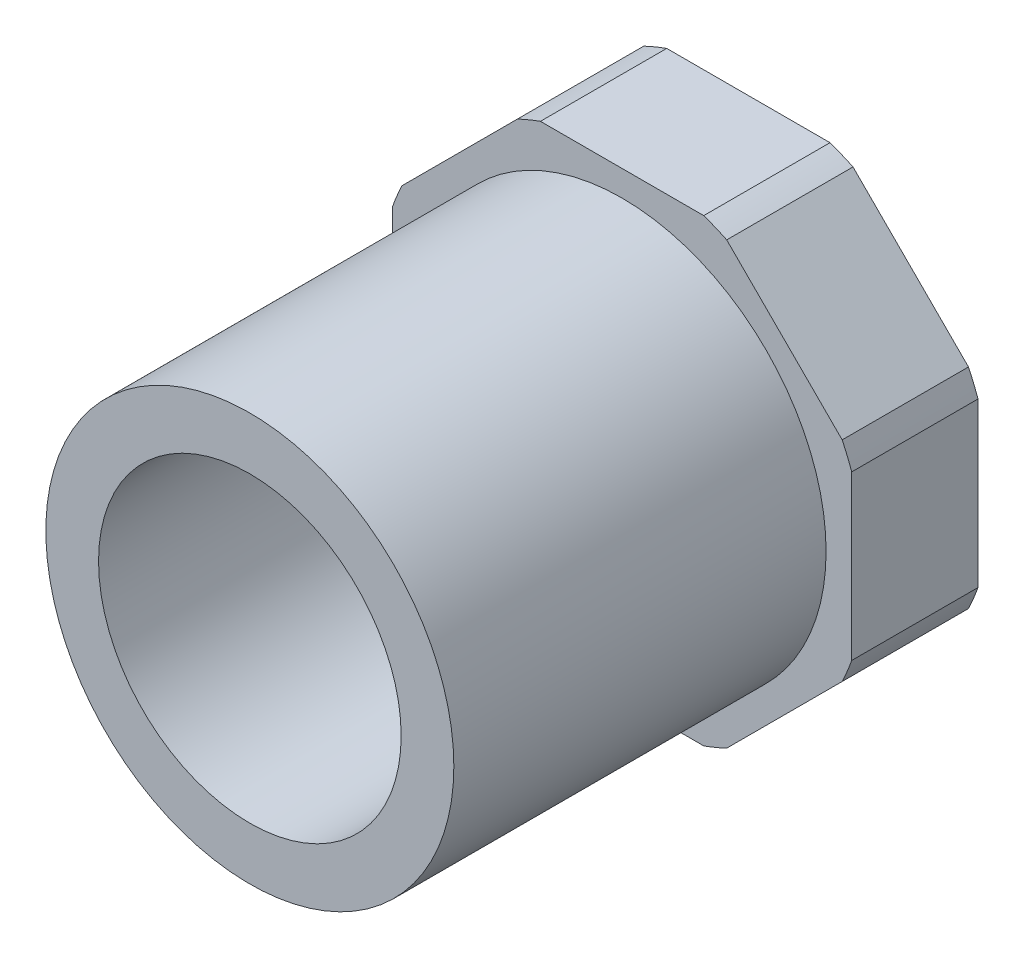
SolidWorks part; units mm, degrees
ref_plane "Front Plane" through (0, 0, 0) normal (0, 0, 1) x (1, 0, 0)
ref_plane "Top Plane" through (0, 0, 0) normal (0, 1, 0) x (1, 0, 0)
ref_plane "Right Plane" through (0, 0, 0) normal (1, 0, 0) x (0, 0, -1)
sketch "Sketch1" plane through (0, 0, 0) normal (1, 0, 0) x (0, 0, -1)
  line L0 (-13.0969, 0) -> (13.0969, 0) construction
  line L1 (6.4611, -10.7188) -> (6.4611, 10.7188) construction
  line L2 (6.4611, -10.7188) -> (-13.0969, -10.7188) construction
  line L3 (-13.0969, -10.7188) -> (-13.0969, -7.9502) construction
  line L4 (-13.0969, -7.9502) -> (4.8736, -7.9502) construction
  line L5 (6.4611, 10.7188) -> (-13.0969, 10.7188) construction
  line L6 (-13.0969, 10.7188) -> (-13.0969, 7.9502) construction
  line L7 (-13.0969, 7.9502) -> (4.8736, 7.9502) construction
  arc A3 (4.8736, -7.9502) -> (4.8736, 7.9502) centre (-14.2399, 0) ccw construction
  point P4 (0, 0)
  point P8 (-13.0969, 0)
  point P9 (6.4611, 0)
  dimension "Wall Thickness" = 2.7686
  dimension "D1" = 1.5875
  dimension "ID" = 15.9004
  dimension "Length" = 26.1937
  dimension "Socket Length" = 19.558
  dimension "OD" = 21.4376
sketch "Sketch2" plane through (0, 0, 0) normal (0, 0, 1) x (1, 0, 0)
  line L0 (0, 12.065) -> (0, -12.065) construction
  circle A1 centre (0, 0) radius 10.7188 construction
  point P5 (0, 0)
  point P12 (0, -10.7188)
  point P14 (10.7188, 0)
  point P15 (-10.7188, 0)
  point P16 (0, 10.7188)
  dimension "D1" = 21.4376
  dimension "Drive Size" = 24.13
sketch "Sketch3" plane through (0, 0, 0) normal (1, 0, 0) x (0, 0, -1)
  line L0 (6.4611, 0) -> (13.0969, 0)
  line L1 (13.0969, 0) -> (13.0969, -10.7188)
  line L2 (13.0969, -10.7188) -> (-13.0969, -10.7188)
  line L3 (-13.0969, -10.7188) -> (-13.0969, -7.9502)
  line L4 (-13.0969, -7.9502) -> (4.8736, -7.9502)
  arc A4 (4.8736, -7.9502) -> (4.8736, 7.9502) centre (-14.2399, 0) ccw construction
  arc A5 (4.8736, -7.9502) -> (6.4611, 0) centre (-14.2399, 0) ccw
revolve "Revolve1" add sketch "Sketch3" angle 360 about L0
sketch "Sketch4" plane through (0, 0, -13.0969) normal (0, 0, -1) x (-1, 0, 0)
  line L0 (-4.9975, 12.065) -> (4.9975, -12.065) construction
  line L3 (4.9975, 12.065) -> (-4.9975, 12.065)
  line L4 (-4.9975, 12.065) -> (-12.065, 4.9975)
  line L20 (-12.065, 4.9975) -> (-12.065, -4.9975)
  line L21 (-12.065, -4.9975) -> (-4.9975, -12.065)
  line L22 (-4.9975, -12.065) -> (4.9975, -12.065)
  line L23 (4.9975, -12.065) -> (12.065, -4.9975)
  line L24 (12.065, -4.9975) -> (12.065, 4.9975)
  line L25 (12.065, 4.9975) -> (4.9975, 12.065)
  circle A2 centre (0, 0) radius 12.065 construction
  circle A3 centre (0, 0) radius 10.7188 construction
  circle A4 centre (0, 0) radius 10.7188
extrude "Boss-Extrude1" add sketch "Sketch4" against normal up to vertex (6.6357 mm away) up to point (0, 10.7188, -6.4611)
ref_plane "Plane1" through (0, 0, 0) normal (0.9239, -0.3827, 0) x (0, 0, -1)
sketch "Sketch5" plane through (0, 0, 0) normal (0.9239, -0.3827, 0) x (0, 0, -1)
  line L1 (6.4611, 13.0591) -> (13.0969, 13.0591)
  line L2 (6.4611, 13.0591) -> (6.4611, 12.8051)
  line L3 (6.4611, 12.8051) -> (13.0969, 12.8051)
  line L4 (13.0969, 13.0591) -> (13.0969, 12.8051)
  dimension "D1" = 0.254
revolve "Cut-Revolve1" cut sketch "Sketch5" angle 360 about axis through (0, 0, 13.0969) along (0, 0, 1)
extrude "Cut-Extrude1" cut sketch "Sketch6" against normal blind 50.8 from surface at 26.1938 starting at face at (10.7188, 0, 13.0969)
sketch "Sketch6" plane through (-8.1031, -57.6063, -13.0969) normal (0, 0, 1) x (1, 0, 0)
  circle A0 centre (8.1031, 57.6063) radius 1.9844
  circle A1 centre (48.4256, 57.6063) radius 1.9844
equation "\"D1\"= \"Drive Length@Sketch1\""
equation "\"D1@Sketch2\"= \"OD@Sketch1\""
